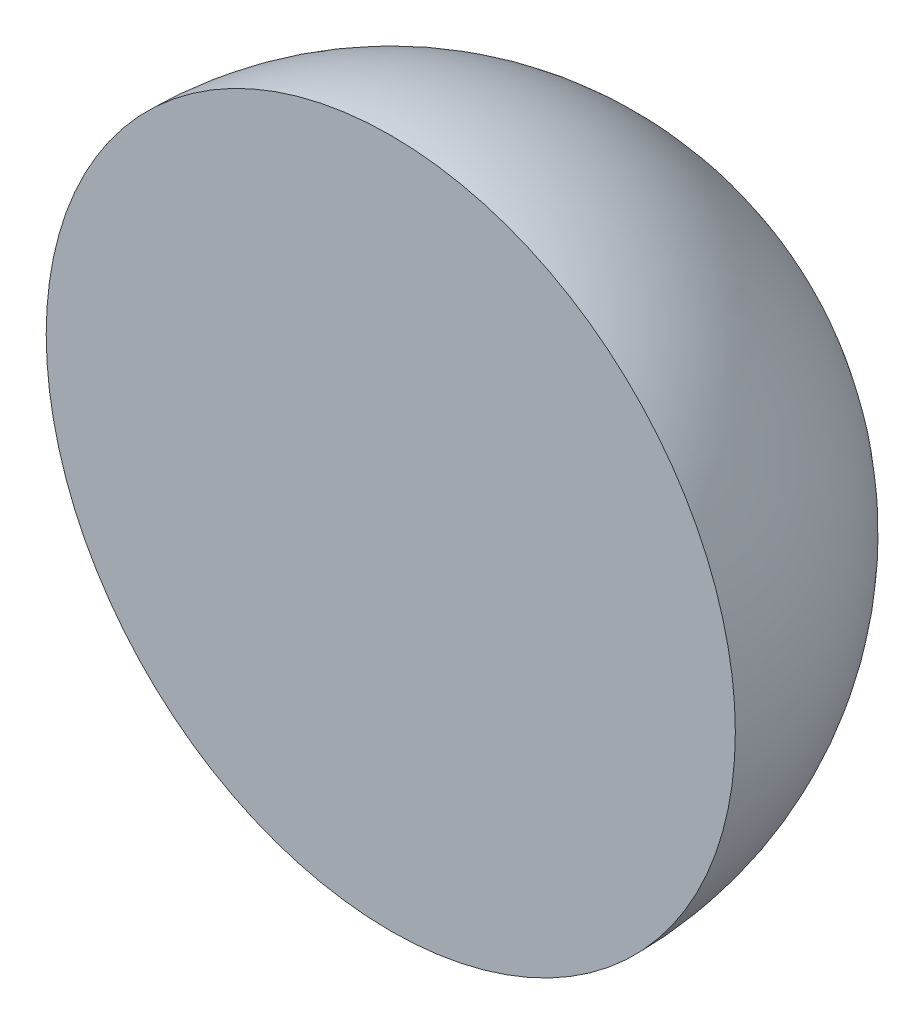
SolidWorks part; units mm, degrees
ref_plane "Front Plane" through (0, 0, 0) normal (0, 0, 1) x (1, 0, 0)
ref_plane "Top Plane" through (0, 0, 0) normal (0, 1, 0) x (1, 0, 0)
ref_plane "Right Plane" through (0, 0, 0) normal (1, 0, 0) x (0, 0, -1)
sketch "Sketch1" plane through (0, 0, 0) normal (1, 0, 0) x (0, 0, -1)
  line L0 (-3.0838, 0) -> (9.4324, 0) construction
  line L1 (0, 8.2669) -> (0, -9.5092) construction
  line L2 (0, 5.9944) -> (0, 0)
  line L3 (0, 0) -> (5.9944, 0)
  arc A0 (5.9944, 0) -> (0, 5.9944) centre (0, 0) ccw
  dimension "D1" = 11.9888
revolve "Revolve1" add sketch "Sketch1" angle 360 about L0
scale "Scale1" scale about centroid uniform scaling yes scale factor 0.6
